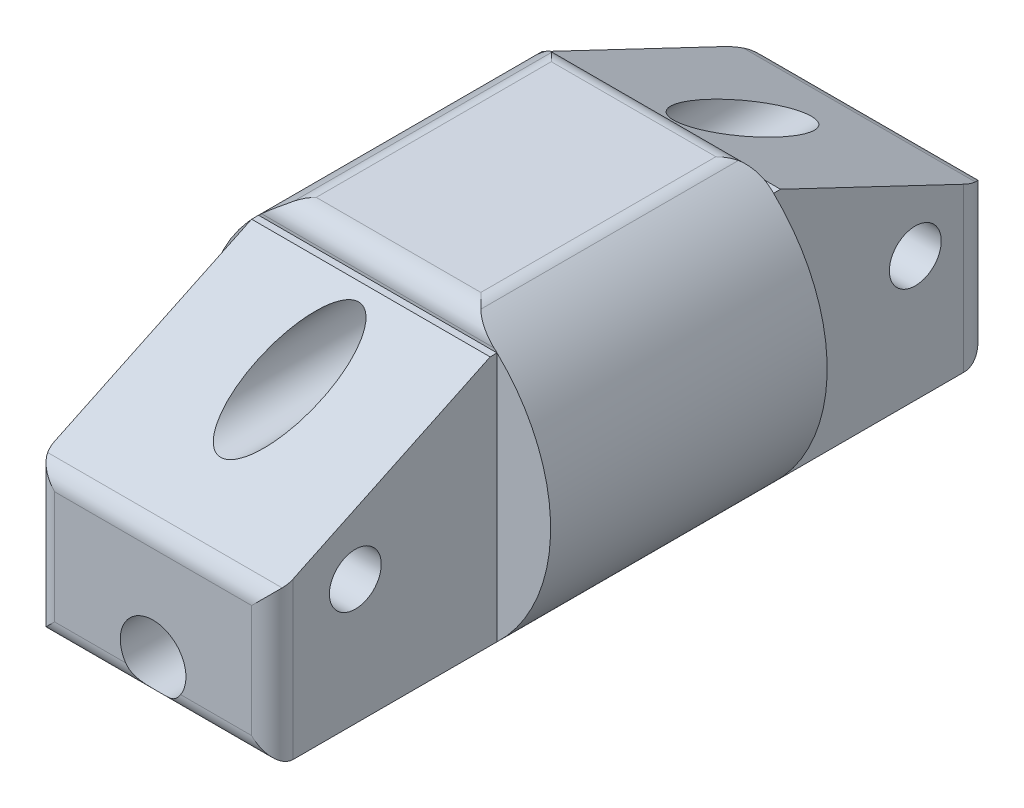
SolidWorks part; units mm, degrees
ref_plane "Front Plane" through (0, 0, 0) normal (0, 0, 1) x (1, 0, 0)
ref_plane "Top Plane" through (0, 0, 0) normal (0, 1, 0) x (1, 0, 0)
ref_plane "Right Plane" through (0, 0, 0) normal (1, 0, 0) x (0, 0, -1)
sketch "Sketch1" plane through (0, 0, 0) normal (0, 0, 1) x (1, 0, 0)
  line L0 (0, 12.7) -> (0, -12.7) construction
  line L1 (-12.7, 0) -> (12.7, 0) construction
  circle A1 centre (0, 0) radius 12.7
  dimension "D1" = 25.4
extrude "FingerBody" add sketch "Sketch1" along normal blind 20.32
ref_plane "MiddleSection" through (0, 0, 10.16) normal (0, 0, -1) x (-1, 0, 0)
ref_plane "CirclePlane" through (0, 0, 0) normal (-1, 0, 0) x (0, -1, 0)
ref_plane "CirclePlane2" through (0, 0, 0) normal (0, -1, 0) x (1, 0, 0)
sketch "Sketch2" plane through (0, 0, 0) normal (0, 0, -1) x (-1, 0, 0)
  line L0 (8.763, -9.1924) -> (-8.763, -9.1924)
  line L2 (12.7, 0) -> (-12.7, 0) construction
  line L3 (8.763, 9.1924) -> (-8.763, 9.1924)
  line L4 (8.763, -9.1924) -> (8.763, 9.1924)
  line L5 (-8.763, -9.1924) -> (-8.763, 9.1924)
  circle A1 centre (0, 0) radius 12.7 construction
  dimension "D1" = 17.526
  dimension "D2" = 17.526
extrude "Boss-Extrude2" add sketch "Sketch2" along normal blind 16.51
mirror "Mirror1" about plane through (0, 0, 10.16) normal (0, 0, -1) of "Boss-Extrude2"
sketch "Sketch3" plane through (0, 0, 36.83) normal (0, 0, 1) x (1, 0, 0)
  line L0 (0, 9.1924) -> (0, -9.1924) construction
  line L1 (-8.763, 9.1924) -> (8.763, 9.1924) construction
  line L2 (8.763, -9.1924) -> (-8.763, -9.1924) construction
  circle A0 centre (0, 0) radius 6.5251
sketch "Sketch4" plane through (-8.763, 0, 0) normal (-1, 0, 0) x (0, 0, 1)
  line L0 (30.734, -9.1924) -> (30.734, 9.1924) construction
  line L3 (36.83, -9.1924) -> (20.32, -9.1924) construction
  line L6 (36.83, 9.1924) -> (20.32, 9.1924) construction
  line L7 (20.32, 0) -> (30.734, 0) construction
  line L8 (20.32, -9.1924) -> (20.32, 9.1924) construction
  circle A0 centre (30.734, 0) radius 1.905
  dimension "D1" = 10.414
extrude "Cut-Extrude2" cut sketch "Sketch4" against normal through all
mirror "Mirror2" about plane through (0, 0, 10.16) normal (0, 0, -1) of "Cut-Extrude2"
sketch "Sketch5" plane through (8.763, 0, 0) normal (1, 0, 0) x (0, 0, -1)
  line L0 (16.51, 1.5724) -> (0.508, 9.1924)
  line L1 (16.51, 9.1924) -> (16.51, -9.1924) construction
  line L2 (16.51, 9.1924) -> (0, 9.1924) construction
  line L3 (0.508, 9.1924) -> (16.51, 9.1924)
  line L4 (16.51, 9.1924) -> (16.51, 1.5724)
  dimension "D1" = 7.62
  dimension "D2" = 16.002
extrude "Cut-Extrude3" cut sketch "Sketch5" against normal through all
fillet "Fillet2" radius 2.54 4 edges at (0, -9.1924, -16.51) (8.763, -3.81, -16.51) (-8.763, -3.81, -16.51) (0, 1.5724, -16.51)
mirror "Mirror6" about plane through (0, 0, 10.16) normal (0, 0, -1) of "Cut-Extrude3"
sketch "Sketch8" plane through (0, 0, 0) normal (0, 0, -1) x (-1, 0, 0)
  line L0 (6.4807, 10.922) -> (-6.4807, 10.922)
  line L1 (12.7, 0) -> (-12.7, 0) construction
  circle A0 centre (0, 0) radius 12.7 construction
  arc A1 (6.4807, 10.922) -> (-6.4807, 10.922) centre (0, 0) ccw
  point P2 (0, 10.922)
  dimension "D1" = 10.922
extrude "Cut-Extrude5" cut sketch "Sketch8" against normal through all both and the other way through all
mirror "Mirror7" about plane through (0, 0, 0) normal (0, -1, 0) of "Cut-Extrude5"
fillet "Fillet3" radius 1.524 4 edges at (6.4807, 10.922, 10.16) (-6.4807, 10.922, 10.16) (0, 10.922, 0) (0, 10.922, 20.32)
fillet "Fillet4" radius 1.524 4 edges at (0, -10.922, 20.32) (-6.4807, -10.922, 10.16) (6.4807, -10.922, 10.16) (0, -10.922, 0)
fillet "Fillet6" radius 1.524 4 edges at (0, -9.1924, 36.83) (-8.763, -3.81, 36.83) (0, 1.5724, 36.83) (8.763, -3.81, 36.83)
sketch "Sketch11" plane through (0, 0, 20.32) normal (0, 0, 1) x (1, 0, 0)
  line L0 (0, 0) -> (-12.7, 0) construction
  line L1 (0, 0) -> (0, -12.7) construction
  line L2 (0, 0) -> (0, 12.6488) construction
  circle A0 centre (0, 0) radius 12.7 construction
  circle A1 centre (0, 6.35) radius 2.413
  circle A2 centre (0, -6.35) radius 2.413
  dimension "D1" = 6.35
  dimension "D2" = 6.35
extrude "Cut-Extrude6" cut sketch "Sketch11" against normal through all and the other way through all
